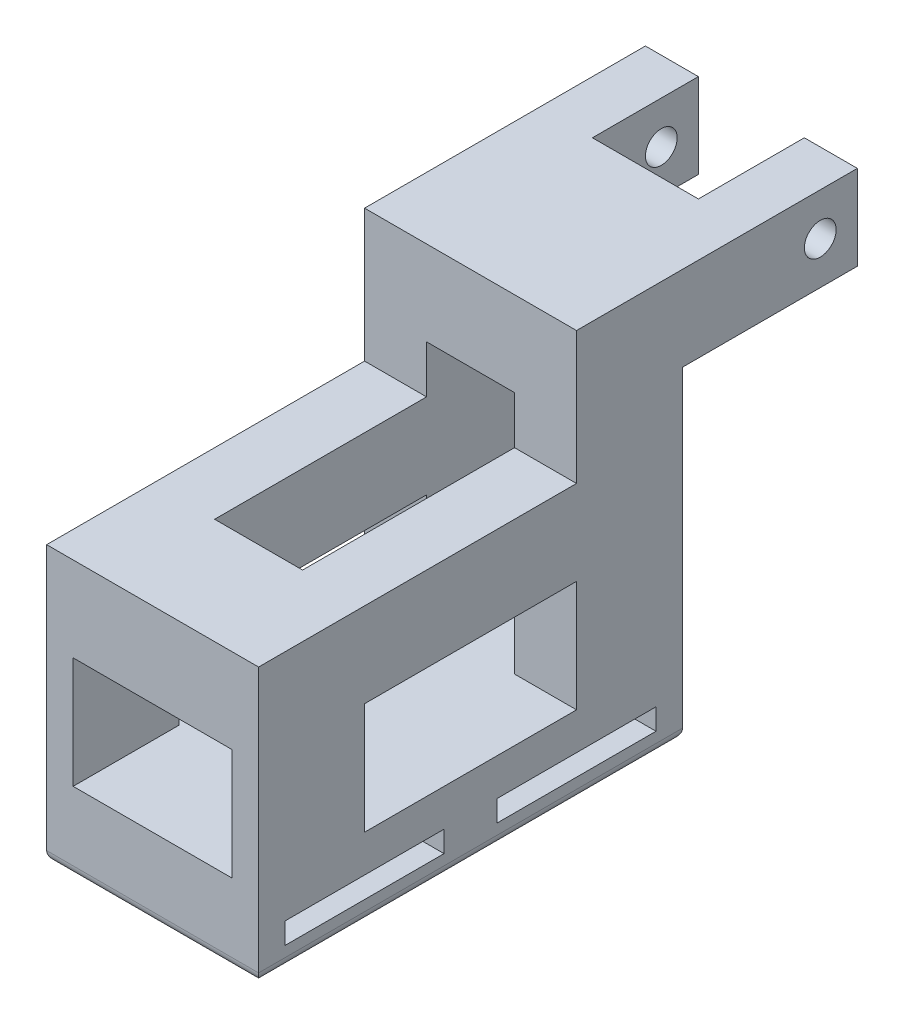
SolidWorks part; units mm, degrees
ref_plane "Alzado" through (0, 0, 0) normal (0, 0, 1) x (1, 0, 0)
ref_plane "Planta" through (0, 0, 0) normal (0, 1, 0) x (1, 0, 0)
ref_plane "Vista lateral" through (0, 0, 0) normal (1, 0, 0) x (0, 0, -1)
sketch "Croquis1" plane through (0, 0, 0) normal (1, 0, 0) x (0, 0, -1)
  line L0 (0, 19.25) -> (0, 11.25) construction
  line L9 (0, 19.25) -> (-58, 19.25) construction
  line L18 (0, 19.25) -> (0, -19.25) construction
  line L19 (0, -19.25) -> (-58, -19.25) construction
  line L20 (-58, 6.75) -> (-58, -19.25)
  line L25 (0, 11.25) -> (-18, 11.25) construction
  line L26 (0, 11.25) -> (0, -11.75) construction
  line L27 (0, -11.75) -> (-28, -11.75) construction
  line L28 (-28, -1.25) -> (-28, -11.75)
  line L29 (0, -11.75) -> (0, -19.25) construction
  line L31 (-1.5, 19.25) -> (-1.5, 11.25)
  line L32 (-18, 11.25) -> (-1.5, 11.25)
  line L33 (-18, -11.75) -> (-18, -19.25)
  line L35 (-58, -19.25) -> (-18, -19.25)
  line L36 (-18, -11.75) -> (-18, 11.25)
  line L38 (-28, -11.75) -> (-48, -11.75)
  line L40 (-28, 19.25) -> (-1.5, 19.25)
  line L54 (-48, -1.25) -> (-48, -11.75)
  line L55 (-28, -1.25) -> (-48, -1.25)
  line L57 (-28, 6.75) -> (-58, 6.75)
  line L58 (-28, 6.75) -> (-28, 19.25)
  line L59 (-28, 19.25) -> (-58, 19.25) construction
  line L60 (-58, 6.75) -> (-58, 19.25) construction
  circle A0 centre (-5, 15.25) radius 1.5
  point P9 (0, 0)
  point P12 (0, 15.25)
  point P13 (-14, -11.75)
  dimension "D6" = 3
  dimension "D1" = 58
  dimension "D2" = 23
  dimension "D3" = 7.5
  dimension "D4" = 8
  dimension "D5" = 10
  dimension "D7" = 5
  dimension "D8" = 3
  dimension "D9" = 40
  dimension "D10" = 10
  dimension "D11" = 10.5
  dimension "D12" = 8
extrude "Saliente-Extruir1" add sketch "Croquis1" along normal mid plane 20
sketch "Croquis2" plane through (0, 19.25, 0) normal (0, 1, 0) x (1, 0, 0)
  line L0 (10, -1.5) -> (-10, -1.5) construction
  line L8 (-5, -1.5) -> (5, -1.5)
  line L9 (-5, -1.5) -> (-5, -11.5)
  line L10 (-5, -11.5) -> (5, -11.5)
  line L11 (5, -1.5) -> (5, -11.5)
  point P4 (-5, -1.5)
  point P6 (0, -1.5)
  point P7 (0, 0)
  point P9 (0, 0)
  dimension "D1" = 10
  dimension "D2" = 10
extrude "Cortar-Extruir1" cut sketch "Croquis2" against normal up to surface (8 mm away) up to face at (0, 11.25, 9.75)
sketch "Croquis5" plane through (0, 0, 58) normal (0, 0, 1) x (1, 0, 0)
  line L0 (10, -11.75) -> (-10, -11.75) construction
  line L1 (-7.5, -11.75) -> (7.5, -11.75)
  line L2 (-7.5, -11.75) -> (-7.5, -1.25)
  line L3 (-7.5, -1.25) -> (7.5, -1.25)
  line L4 (7.5, -11.75) -> (7.5, -1.25)
  point P8 (0, -11.75)
  dimension "D1" = 15
  dimension "D2" = 10.5
extrude "Cortar-Extruir5" cut sketch "Croquis5" against normal up to surface (10 mm away) up to face at (0, -6.5, 48)
sketch "Croquis4" plane through (0, 0, 0) normal (1, 0, 0) x (0, 0, -1)
  line L0 (-58, -19.25) -> (-18, -19.25) construction
  line L1 (-55.5, -15.25) -> (-40.5, -15.25)
  line L2 (-55.5, -15.25) -> (-55.5, -17.25)
  line L3 (-55.5, -17.25) -> (-40.5, -17.25)
  line L4 (-40.5, -15.25) -> (-40.5, -17.25)
  line L5 (-55.5, -15.25) -> (-40.5, -17.25) construction
  line L6 (-55.5, -17.25) -> (-40.5, -15.25) construction
  line L8 (-35.5, -15.25) -> (-20.5, -15.25)
  line L9 (-35.5, -15.25) -> (-35.5, -17.25)
  line L10 (-35.5, -17.25) -> (-20.5, -17.25)
  line L11 (-20.5, -15.25) -> (-20.5, -17.25)
  line L13 (-58, 6.75) -> (-58, -19.25) construction
  line L14 (-18, -19.25) -> (-18, 11.25) construction
  point P0 (-48, -16.25)
  point P7 (-46.1316, -16.25)
  point P15 (-58.7395, -12.0198)
  point P16 (-59.5173, -19.9202)
  point P17 (-28, -17.25)
  dimension "D1" = 2
  dimension "D2" = 2
  dimension "D3" = 15
  dimension "D4" = 10
  dimension "D5" = 10
extrude "Cortar-Extruir4" cut sketch "Croquis4" against normal through all both and the other way through all
sketch "Croquis3" plane through (0, 0, 18) normal (0, 0, 1) x (1, 0, 0)
  line L7 (10, -19.25) -> (-10, -19.25) construction
  line L13 (10, 11.25) -> (-10, 11.25) construction
  line L14 (4.15, -11.75) -> (-4.15, -11.75)
  line L15 (4.15, -11.75) -> (4.15, 11.25)
  line L16 (4.15, 11.25) -> (-4.15, 11.25)
  line L17 (-4.15, -11.75) -> (-4.15, 11.25)
  point P8 (0, 11.25)
  dimension "D2" = 7.5
  dimension "D1" = 8.3
extrude "Cortar-Extruir3" cut sketch "Croquis3" along normal up to surface (30 mm away) up to face at (-8.75, -6.5, 48)
fillet "Redondeo2" radius 1 4 edges at (0, -19.25, 58) (10, -19.25, 38) (0, -19.25, 18) (-10, -19.25, 38)
